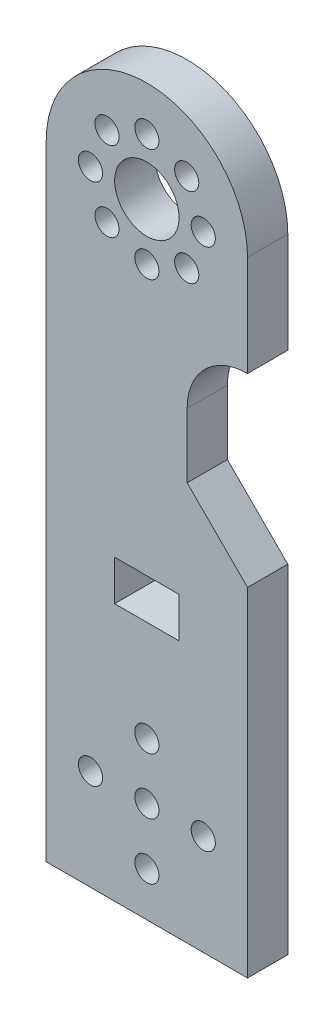
SolidWorks part; units mm, degrees
ref_plane "Front Plane" through (0, 0, 0) normal (0, 0, 1) x (1, 0, 0)
ref_plane "Top Plane" through (0, 0, 0) normal (0, 1, 0) x (1, 0, 0)
ref_plane "Right Plane" through (0, 0, 0) normal (1, 0, 0) x (0, 0, -1)
sketch "Sketch1" plane through (0, 0, 0) normal (0, 0, 1) x (1, 0, 0)
  line L6 (-12.5, 0) -> (-12.5, -77.5)
  line L7 (12.5, 0) -> (12.5, -77.5)
  line L12 (0, -77.5) -> (-12.5, -77.5) construction
  line L13 (0, -77.5) -> (12.5, -77.5) construction
  line L15 (-12.5, -77.5) -> (12.5, -77.5)
  circle A1 centre (0, 0) radius 4
  circle A8 centre (0, 7) radius 1.5
  circle A15 centre (4.9497, 4.9497) radius 1.5
  circle A16 centre (7, 0) radius 1.5
  circle A17 centre (4.9497, -4.9497) radius 1.5
  circle A18 centre (0, -7) radius 1.5
  circle A19 centre (-4.9497, -4.9497) radius 1.5
  circle A20 centre (-7, 0) radius 1.5
  circle A21 centre (-4.9497, 4.9497) radius 1.5
  arc A22 (12.5, 0) -> (-12.5, 0) centre (0, 0) ccw
  point P8 (0, 12.5)
  point P24 (0, 0)
  dimension "D2" = 8
  dimension "D3" = 3
  dimension "D4" = 7
  dimension "D5" = 8
  dimension "D6" = 90
  dimension "D7" = 25
  dimension "D13" = 12.5
  dimension "D14" = 12.5
extrude "Boss-Extrude1" add sketch "Sketch1" along normal blind 5
sketch "Sketch2" plane through (0, 0, 5) normal (0, 0, 1) x (1, 0, 0)
  line L0 (0, -8.5) -> (0, -77.5) construction
  line L1 (-12.5, -77.5) -> (12.5, -77.5) construction
  line L6 (0, -77.5) -> (0, -43) construction
  line L7 (0, -43) -> (12.5, -43) construction
  line L8 (12.5, 0) -> (12.5, -77.5) construction
  line L10 (-4, -40.5) -> (4, -40.5)
  line L11 (-4, -40.5) -> (-4, -45.5)
  line L12 (-4, -45.5) -> (4, -45.5)
  line L13 (4, -40.5) -> (4, -45.5)
  line L14 (-4, -40.5) -> (4, -45.5) construction
  line L15 (-4, -45.5) -> (4, -40.5) construction
  circle A1 centre (0, -7) radius 1.5 construction
  dimension "D1" = 8
  dimension "D2" = 5
extrude "Cut-Extrude1" cut sketch "Sketch2" against normal blind 10
sketch "Sketch3" plane through (0, 0, 5) normal (0, 0, 1) x (1, 0, 0)
  line L0 (-12.5, -77.5) -> (-12.5, -52.5) construction
  line L1 (-12.5, 0) -> (-12.5, -77.5) construction
  line L2 (-12.5, -65) -> (12.5, -65) construction
  line L5 (-12.5, -52.5) -> (12.5, -52.5)
  line L6 (-12.5, -52.5) -> (-12.5, -77.5)
  line L7 (-12.5, -77.5) -> (12.5, -77.5)
  line L8 (12.5, -52.5) -> (12.5, -77.5)
  line L9 (-12.5, -52.5) -> (12.5, -77.5) construction
  line L10 (-12.5, -77.5) -> (12.5, -52.5) construction
  circle A0 centre (0, -65) radius 1.5
  circle A1 centre (0, -58) radius 1.5
  circle A2 centre (-58, 0) radius 1.5
  circle A3 centre (0, 58) radius 1.5
  circle A4 centre (58, 0) radius 1.5
  circle A5 centre (-7, -65) radius 1.5
  circle A6 centre (7, -65) radius 1.5
  circle A7 centre (0, -72) radius 1.5
  point P8 (-65, 0)
  point P9 (0, -65)
  point P18 (0, 65)
  point P23 (65, 0)
  point P26 (0, 0)
  point P37 (0, -65)
  dimension "D4" = 3
  dimension "D1" = 25
  dimension "D2" = 25
  dimension "D3" = 25
  dimension "D5" = 7
  dimension "D6" = 4
extrude "Cut-Extrude2" cut sketch "Sketch3" against normal blind 10
ref_plane "Plane1" through (0, 0, 5) normal (0, 0, 1) x (1, 0, 0)
sketch "Sketch4" plane through (0, 0, 5) normal (0, 0, 1) x (1, 0, 0)
  line L0 (12.5, 0) -> (12.5, -77.5) construction
  line L1 (5, -20) -> (5, -28)
  line L2 (5, -28) -> (12.5, -35.5)
  line L5 (12.5, -20) -> (12.5, -12.5) construction
  line L6 (12.5, -12.5) -> (12.5, -27.5) construction
  line L7 (12.5, -20) -> (5, -20) construction
  line L8 (12.5, -27.5) -> (12.5, -35.5)
  circle A0 centre (0, 0) radius 12.5
  arc A1 (12.5, -27.5) -> (5, -20) centre (12.5, -20) ccw
  dimension "D1" = 25
  dimension "D2" = 15
  dimension "D3" = 20
  dimension "D4" = 8
  dimension "D5" = 45
extrude "Cut-Extrude3" cut sketch "Sketch4" against normal blind 10 contours A1 L1 L2 L8
